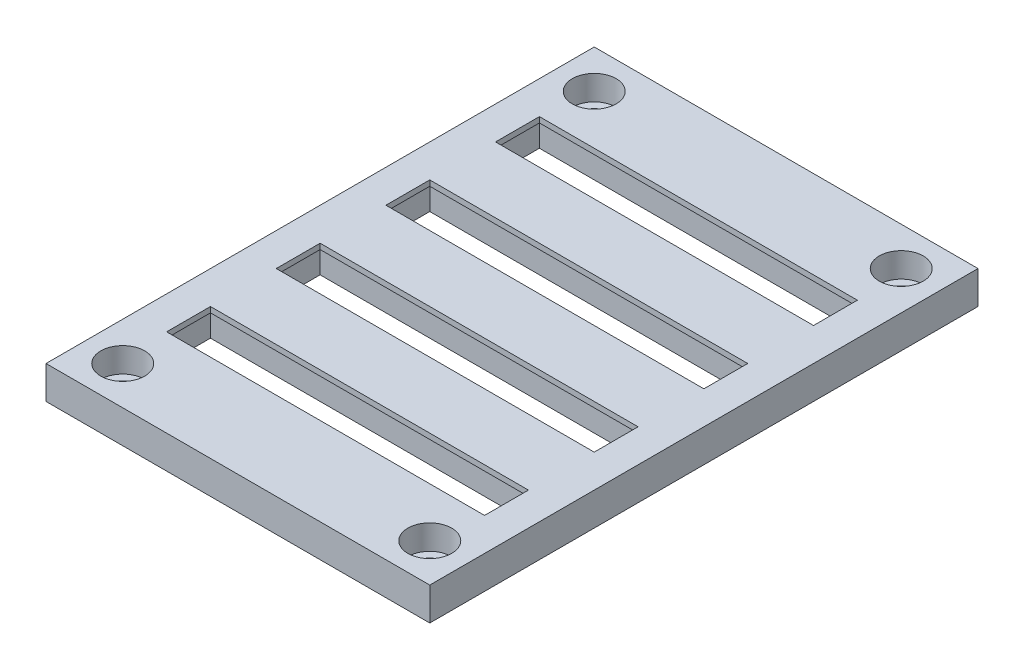
SolidWorks part; units mm, degrees
ref_plane "Front Plane" through (0, 0, 0) normal (0, 0, 1) x (1, 0, 0)
ref_plane "Top Plane" through (0, 0, 0) normal (0, 1, 0) x (1, 0, 0)
ref_plane "Right Plane" through (0, 0, 0) normal (1, 0, 0) x (0, 0, -1)
sketch "Sketch1" plane through (0, 0, 0) normal (0, 1, 0) x (1, 0, 0)
  line L1 (0, 0) -> (70, 0)
  line L2 (0, 0) -> (0, 100)
  line L3 (0, 100) -> (70, 100)
  line L4 (70, 0) -> (70, 100)
  dimension "D1" = 70
  dimension "D2" = 100
extrude "Boss-Extrude1" add sketch "Sketch1" along normal blind 6
sketch "Sketch3" plane through (0, 0, 0) normal (0, -1, 0) x (1, 0, 0)
  line L8 (0, 0) -> (70, 0) construction
  line L9 (5, -15) -> (65, -15)
  line L10 (5, -15) -> (5, -25)
  line L11 (5, -25) -> (65, -25)
  line L12 (65, -15) -> (65, -25)
  line L13 (0, -100) -> (0, 0) construction
  line L30 (5, -35) -> (5, -45)
  line L31 (5, -35) -> (65, -35)
  line L32 (65, -35) -> (65, -45)
  line L33 (5, -45) -> (65, -45)
  line L34 (5, -55) -> (5, -65)
  line L35 (5, -55) -> (65, -55)
  line L36 (65, -55) -> (65, -65)
  line L37 (5, -65) -> (65, -65)
  line L38 (5, -75) -> (5, -85)
  line L39 (5, -75) -> (65, -75)
  line L40 (65, -75) -> (65, -85)
  line L41 (5, -85) -> (65, -85)
  line L42 (5, -15) -> (5, -35) construction
  dimension "D1" = 15
  dimension "D2" = 60
  dimension "D3" = 5
  dimension "D4" = 10
  dimension "D6" = 20
  dimension "D5" = 4
extrude "Cut-Extrude1" cut sketch "Sketch3" against normal blind 5
sketch "Sketch4" plane through (0, 5, 0) normal (0, -1, 0) x (1, 0, 0)
  line L0 (65, -15) -> (5, -15) construction
  line L1 (6, -16) -> (64, -16)
  line L2 (6, -16) -> (6, -24)
  line L3 (6, -24) -> (64, -24)
  line L4 (64, -16) -> (64, -24)
  line L5 (5, -25) -> (65, -25) construction
  line L6 (65, -25) -> (65, -15) construction
  line L7 (5, -15) -> (5, -25) construction
  line L8 (6, -36) -> (6, -44)
  line L9 (6, -36) -> (64, -36)
  line L10 (64, -36) -> (64, -44)
  line L11 (6, -44) -> (64, -44)
  line L12 (6, -56) -> (6, -64)
  line L13 (6, -56) -> (64, -56)
  line L14 (64, -56) -> (64, -64)
  line L15 (6, -64) -> (64, -64)
  line L16 (6, -76) -> (6, -84)
  line L17 (6, -76) -> (64, -76)
  line L18 (64, -76) -> (64, -84)
  line L19 (6, -84) -> (64, -84)
  dimension "D1" = 1
  dimension "D2" = 1
  dimension "D3" = 1
  dimension "D4" = 1
  dimension "D5" = 4
extrude "Cut-Extrude2" cut sketch "Sketch4" against normal blind 1
sketch "Sketch5" plane through (0, 0, 0) normal (0, -1, 0) x (1, 0, 0)
  line L0 (70, 0) -> (70, -100) construction
  line L1 (0, 0) -> (70, 0) construction
  line L2 (0, -50) -> (70, -50) construction
  line L4 (0, -100) -> (0, 0) construction
  line L5 (35, 0) -> (35, -100) construction
  line L6 (70, -100) -> (0, -100) construction
  circle A0 centre (63, -7) radius 2.5
  circle A1 centre (7, -7) radius 2.5
  circle A2 centre (63, -93) radius 2.5
  circle A3 centre (7, -93) radius 2.5
  dimension "D1" = 5
  dimension "D2" = 7
  dimension "D3" = 7
extrude "Cut-Extrude3" cut sketch "Sketch5" against normal blind 10
sketch "Sketch6" plane through (0, 6, 0) normal (0, 1, 0) x (1, 0, 0)
  line L0 (35, 100) -> (35, 0) construction
  line L1 (70, 100) -> (0, 100) construction
  line L2 (0, 0) -> (70, 0) construction
  line L3 (0, 50) -> (70, 50) construction
  line L4 (0, 100) -> (0, 0) construction
  line L5 (70, 0) -> (70, 100) construction
  circle A0 centre (7, 93) radius 4
  circle A1 centre (63, 93) radius 4
  circle A2 centre (63, 7) radius 4
  circle A3 centre (7, 7) radius 4
  dimension "D1" = 8
extrude "Cut-Extrude4" cut sketch "Sketch6" against normal blind 4.5
